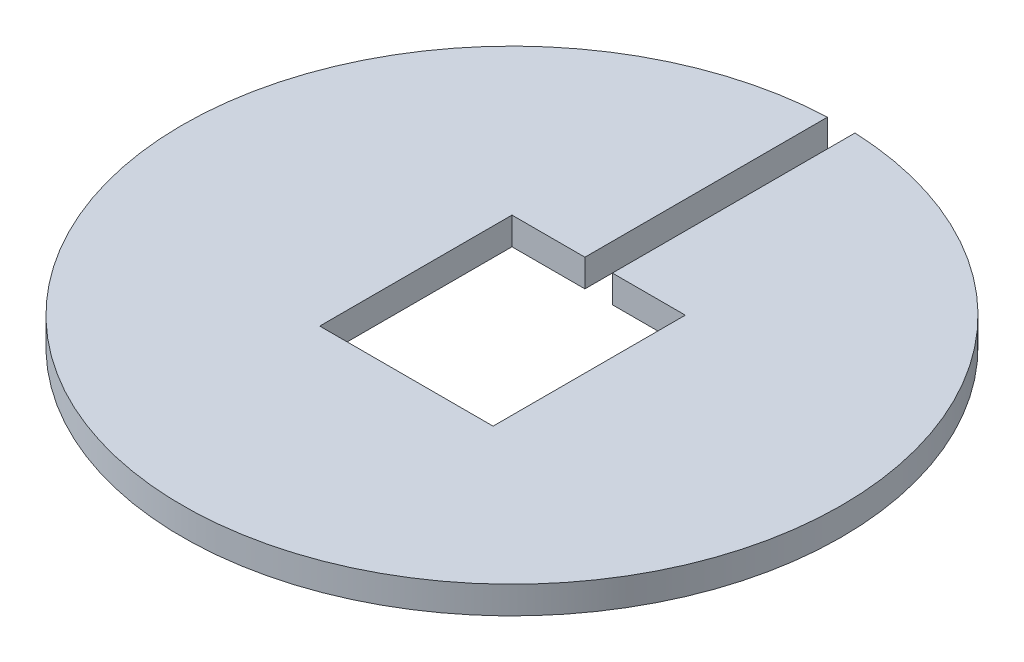
SolidWorks part; units mm, degrees
ref_plane "Front Plane" through (0, 0, 0) normal (0, 0, 1) x (1, 0, 0)
ref_plane "Top Plane" through (0, 0, 0) normal (0, 1, 0) x (1, 0, 0)
ref_plane "Right Plane" through (0, 0, 0) normal (1, 0, 0) x (0, 0, -1)
sketch "Sketch1" plane through (0, 0, 0) normal (0, 1, 0) x (1, 0, 0)
  line L2 (-4.9135, 7.7612) -> (-4.9135, 35.8079)
  line L3 (-1.7385, 7.7612) -> (-1.7385, 35.8079)
  line L4 (-1.7385, 7.7612) -> (6.6943, 7.7612)
  line L5 (-13.3463, 7.7612) -> (-4.9135, 7.7612)
  line L6 (-13.3463, 7.7612) -> (-13.3463, -14.4638)
  line L7 (-13.3463, -14.4638) -> (6.6943, -14.4638)
  line L8 (6.6943, 7.7612) -> (6.6943, -14.4638)
  arc A0 (-4.9135, 35.8079) -> (-1.7385, 35.8079) centre (-3.326, -2.2591) ccw
  dimension "D1" = 76.2
  dimension "D2" = 20.0406
  dimension "D4" = 22.225
  dimension "D5" = 10.0203
  dimension "D6" = 10.0203
extrude "Boss-Extrude1" add sketch "Sketch1" along normal blind 3.175
